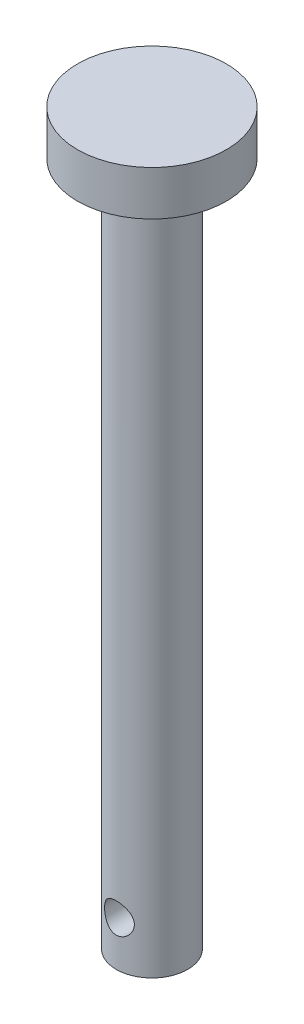
SolidWorks part; units mm, degrees
ref_plane "Front Plane" through (0, 0, 0) normal (0, 0, 1) x (1, 0, 0)
ref_plane "Top Plane" through (0, 0, 0) normal (0, 1, 0) x (1, 0, 0)
ref_plane "Right Plane" through (0, 0, 0) normal (1, 0, 0) x (0, 0, -1)
sketch "Sketch1" plane through (0, 0, 0) normal (0, 1, 0) x (1, 0, 0)
  circle A0 centre (0, 0) radius 2.4
  dimension "D1" = 4.8
extrude "Boss-Extrude1" add sketch "Sketch1" along normal blind 46
sketch "Sketch2" plane through (0, 46, 0) normal (0, 1, 0) x (1, 0, 0)
  circle A0 centre (0, 0) radius 5
  dimension "D1" = 10
extrude "Boss-Extrude2" add sketch "Sketch2" along normal blind 3
sketch "Sketch3" plane through (0, 0, 0) normal (0, 0, 1) x (1, 0, 0)
  circle A0 centre (0, 3) radius 1
  point P2 (0, 0)
  dimension "D1" = 2
  dimension "D2" = 3
extrude "Cut-Extrude1" cut sketch "Sketch3" against normal through all both and the other way through all
